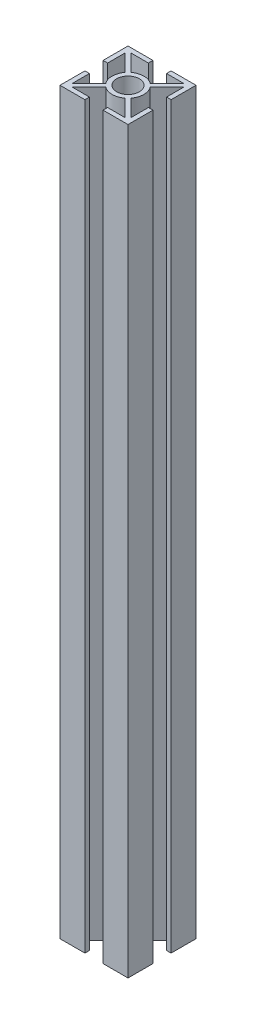
SolidWorks part; units mm, degrees
ref_plane "Front" through (0, 0, 0) normal (0, 0, 1) x (1, 0, 0)
ref_plane "Top" through (0, 0, 0) normal (0, 1, 0) x (1, 0, 0)
ref_plane "Right" through (0, 0, 0) normal (1, 0, 0) x (0, 0, -1)
sketch "Sketch1" plane through (0, 0, 0) normal (0, 1, 0) x (1, 0, 0)
  line L0 (-11.268, -11.268) -> (15.0013, 15.0013) construction
  line L1 (-14.2237, 14.2237) -> (18.9918, -18.9918) construction
  line L2 (4.1919, 5.6061) -> (11.5871, 13.0013)
  line L3 (-6.0914, 0) -> (9.94, 0) construction
  line L4 (13.0013, 11.5871) -> (5.6061, 4.1919)
  line L5 (15.0013, 15.0013) -> (4.0013, 15.0013)
  line L6 (4.0013, 15.0013) -> (4.0013, 13.0013)
  line L7 (4.0013, 13.0013) -> (11.5871, 13.0013)
  line L8 (15.0013, 15.0013) -> (15.0013, 4.0013)
  line L9 (15.0013, 4.0013) -> (13.0013, 4.0013)
  line L10 (13.0013, 4.0013) -> (13.0013, 11.5871)
  line L11 (0, 3.6644) -> (0, -12.3399) construction
  line L12 (4.0013, -13.0013) -> (11.5871, -13.0013)
  line L13 (4.0013, -15.0013) -> (4.0013, -13.0013)
  line L14 (15.0013, -15.0013) -> (4.0013, -15.0013)
  line L15 (15.0013, -15.0013) -> (15.0013, -4.0013)
  line L16 (15.0013, -4.0013) -> (13.0013, -4.0013)
  line L17 (13.0013, -4.0013) -> (13.0013, -11.5871)
  line L18 (13.0013, -11.5871) -> (5.6061, -4.1919)
  line L19 (4.1919, -5.6061) -> (11.5871, -13.0013)
  line L20 (-13.0013, 11.5871) -> (-5.6061, 4.1919)
  line L21 (-4.1919, 5.6061) -> (-11.5871, 13.0013)
  line L22 (-15.0013, 4.0013) -> (-13.0013, 4.0013)
  line L23 (-13.0013, 4.0013) -> (-13.0013, 11.5871)
  line L24 (-15.0013, 15.0013) -> (-15.0013, 4.0013)
  line L25 (-4.0013, 13.0013) -> (-11.5871, 13.0013)
  line L26 (-4.0013, 15.0013) -> (-4.0013, 13.0013)
  line L27 (-15.0013, 15.0013) -> (-4.0013, 15.0013)
  line L28 (-4.1919, -5.6061) -> (-11.5871, -13.0013)
  line L29 (-15.0013, -4.0013) -> (-13.0013, -4.0013)
  line L30 (-13.0013, -4.0013) -> (-13.0013, -11.5871)
  line L31 (-13.0013, -11.5871) -> (-5.6061, -4.1919)
  line L32 (-15.0013, -15.0013) -> (-15.0013, -4.0013)
  line L33 (-15.0013, -15.0013) -> (-4.0013, -15.0013)
  line L34 (-4.0013, -15.0013) -> (-4.0013, -13.0013)
  line L35 (-4.0013, -13.0013) -> (-11.5871, -13.0013)
  arc A0 (4.1919, 5.6061) -> (-4.1919, 5.6061) centre (0, 0) ccw
  circle A1 centre (0, 0) radius 5
  arc A2 (-5.6061, 4.1919) -> (-5.6061, -4.1919) centre (0, 0) ccw
  arc A3 (-4.1919, -5.6061) -> (4.1919, -5.6061) centre (0, 0) ccw
  arc A4 (5.6061, -4.1919) -> (5.6061, 4.1919) centre (0, 0) ccw
  point P9 (14.0013, 4.0013)
  point P12 (4.0013, 14.0013)
  point P21 (4.0013, -14.0013)
  point P27 (14.0013, -4.0013)
  dimension "D1" = 14
  dimension "D2" = 90
  dimension "D6" = 10
  dimension "D3" = 21.215
  dimension "D4" = 11
  dimension "D5" = 11
  dimension "D7" = 2
  dimension "D8" = 1
  dimension "D9" = 2
  dimension "D10" = 2
  dimension "D11" = 45
extrude "Boss-Extrude1" add sketch "Sketch1" along normal blind 326
sketch "Sketch2" plane through (0, 0, 15.0013) normal (0, 0, 1) x (1, 0, 0)
  circle A0 centre (-0.0013, 82) radius 3.3234
extrude "Cut-Extrude1" cut sketch "Sketch2" against normal up to next
